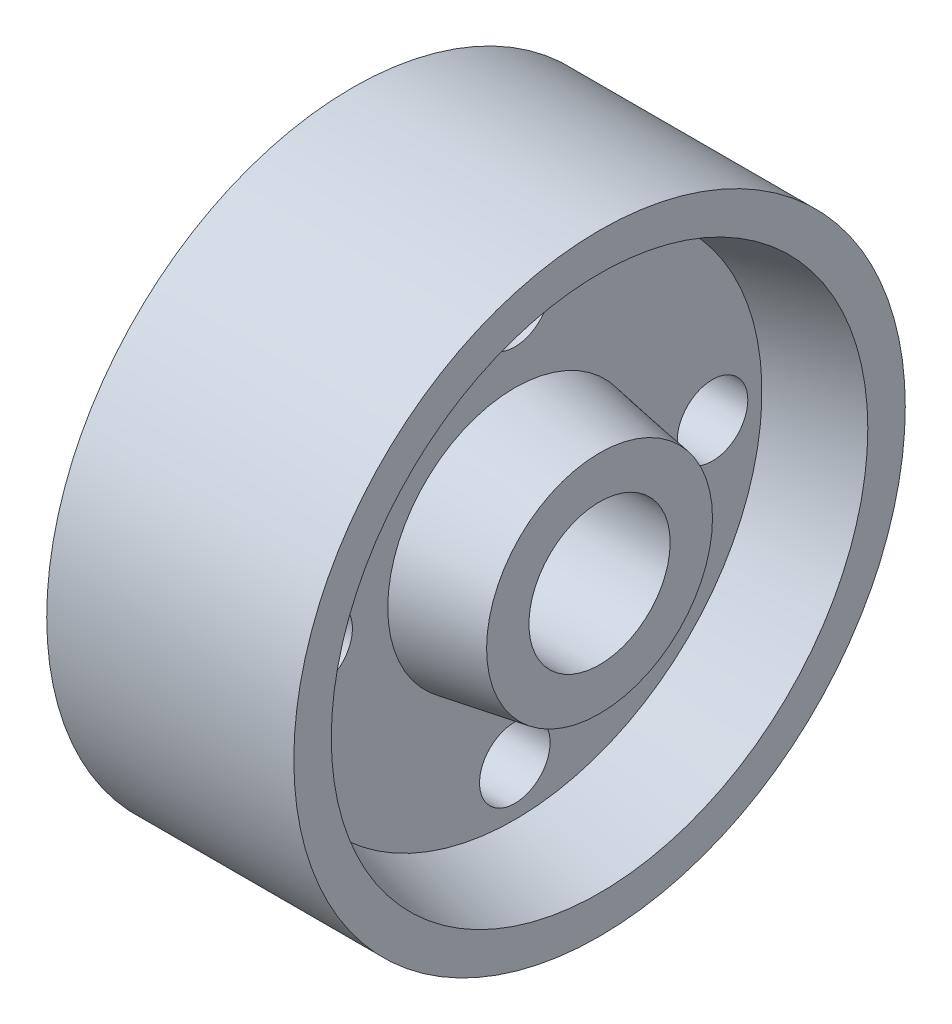
SolidWorks part; units mm, degrees
ref_plane "Front Plane" through (0, 0, 0) normal (0, 0, 1) x (1, 0, 0)
ref_plane "Top Plane" through (0, 0, 0) normal (0, 1, 0) x (1, 0, 0)
ref_plane "Right Plane" through (0, 0, 0) normal (1, 0, 0) x (0, 0, -1)
sketch "Sketch1" plane through (0, 0, 0) normal (0, 1, 0) x (1, 0, 0)
  line L0 (0, 0) -> (35, 0) construction
  line L1 (0, 0) -> (0, 16)
  line L2 (0, 16) -> (12, 18)
  line L3 (12, 18) -> (12, 35)
  line L4 (12, 35) -> (0, 38)
  line L5 (0, 38) -> (0, 43.3072)
  line L6 (0, 43.3072) -> (35, 43.3072)
  line L7 (17.5, 43.3072) -> (17.5, 0) construction
  line L8 (35, 0) -> (35, 16)
  line L9 (35, 16) -> (23, 18)
  line L10 (23, 18) -> (23, 35)
  line L11 (23, 35) -> (35, 38)
  line L12 (35, 38) -> (35, 43.3072)
  line L13 (0, 0) -> (35, 0)
  point P16 (34.3655, 0)
  dimension "D1" = 5.5
  dimension "D2" = 17.5
  dimension "D3" = 38
  dimension "D4" = 35
  dimension "D5" = 18
  dimension "D6" = 16
  dimension "D7" = 43.3072
revolve "Revolve1" add sketch "Sketch1" angle 360 about L13
sketch "Sketch2" plane through (23, 0, 0) normal (1, 0, 0) x (0, 0, -1)
  circle A0 centre (0, 0) radius 28 construction
  circle A1 centre (0, 28) radius 5
  circle A2 centre (28, 0) radius 5
  circle A3 centre (0, -28) radius 5
  circle A4 centre (-28, 0) radius 5
  circle A5 centre (0, 0) radius 18 construction
  point P14 (0, 0)
  dimension "D1" = 56
  dimension "D2" = 10
  dimension "D4" = 28
  dimension "D5" = 56
  dimension "D3" = 4
extrude "Cut-Extrude1" cut sketch "Sketch2" against normal through all
sketch "Sketch3" plane through (35, 0, 0) normal (1, 0, 0) x (0, 0, -1)
  circle A0 centre (0, 0) radius 10
  dimension "D1" = 20
extrude "Cut-Extrude2" cut sketch "Sketch3" against normal through all
